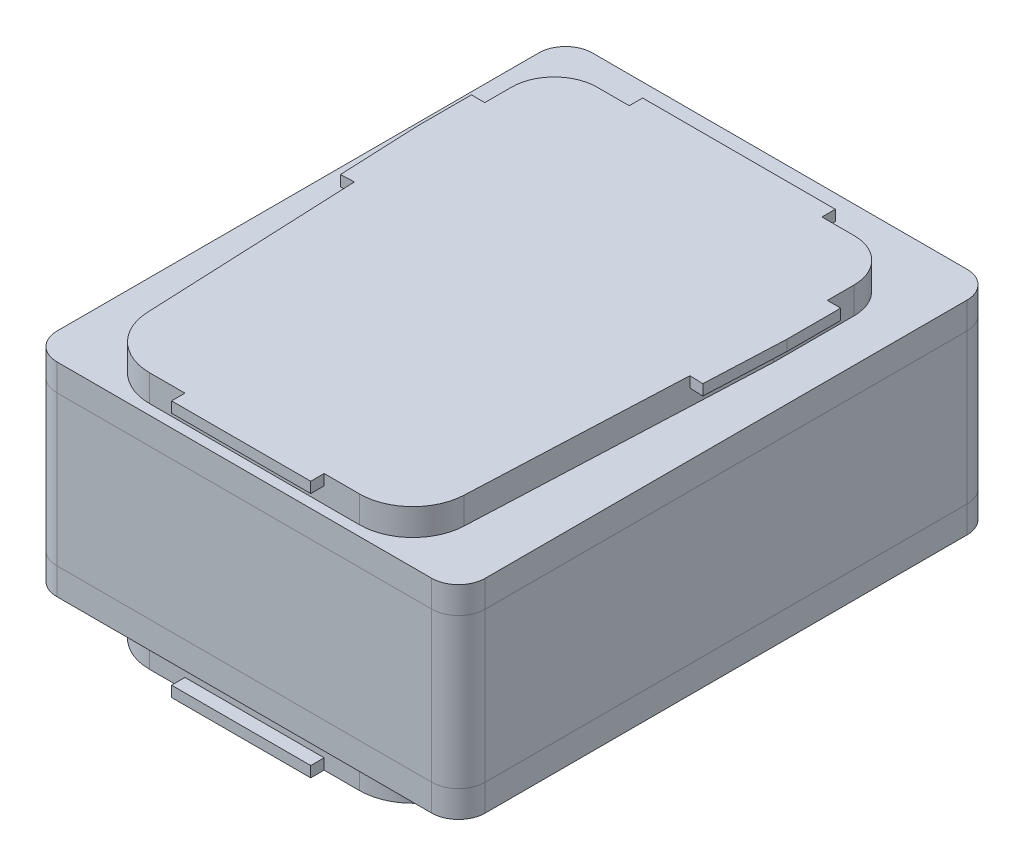
SolidWorks part; units mm, degrees
ref_plane "Front Plane" through (0, 0, 0) normal (0, 0, 1) x (1, 0, 0)
ref_plane "Top Plane" through (0, 0, 0) normal (0, 1, 0) x (1, 0, 0)
ref_plane "Right Plane" through (0, 0, 0) normal (1, 0, 0) x (0, 0, -1)
sketch "Sketch1" plane through (0, 0, 0) normal (0, 1, 0) x (1, 0, 0)
  line L0 (-32, 36) -> (-32, 21)
  line L3 (-24, 44) -> (24, 44)
  line L7 (32, 36) -> (32, 21)
  line L8 (-32, 21) -> (-29.5796, -34.4362)
  line L9 (-19.5891, -44) -> (19.5891, -44)
  line L10 (29.5796, -34.4362) -> (32, 21)
  line L11 (-24, 41) -> (24, 41)
  line L12 (29, 36) -> (29, 21.0655)
  line L13 (26.5825, -34.3053) -> (29, 21.0655)
  line L14 (-19.5891, -41) -> (19.5891, -41)
  line L15 (-29, 21.0655) -> (-26.5825, -34.3053)
  line L16 (-29, 36) -> (-29, 21.0655)
  line L17 (-35, -45.9) -> (35, -45.9)
  line L18 (-40, -40.9) -> (-40, 49.1)
  line L19 (-35, 54.1) -> (35, 54.1)
  line L20 (40, -40.9) -> (40, 49.1)
  arc A2 (-19.5891, -44) -> (-29.5796, -34.4362) centre (-19.5891, -34) cw
  arc A3 (29.5796, -34.4362) -> (19.5891, -44) centre (19.5891, -34) cw
  arc A4 (-24, 44) -> (-32, 36) centre (-24, 36) ccw
  arc A5 (32, 36) -> (24, 44) centre (24, 36) ccw
  arc A6 (29, 36) -> (24, 41) centre (24, 36) ccw
  arc A7 (26.5825, -34.3053) -> (19.5891, -41) centre (19.5891, -34) cw
  arc A8 (-19.5891, -41) -> (-26.5825, -34.3053) centre (-19.5891, -34) cw
  arc A9 (-24, 41) -> (-29, 36) centre (-24, 36) ccw
  arc A10 (-40, -40.9) -> (-35, -45.9) centre (-35, -40.9) ccw
  arc A11 (35, -45.9) -> (40, -40.9) centre (35, -40.9) ccw
  arc A12 (40, 49.1) -> (35, 54.1) centre (35, 49.1) ccw
  arc A13 (-35, 54.1) -> (-40, 49.1) centre (-35, 49.1) ccw
  point P0 (0, 0)
  point P32 (0, 4.1)
  dimension "D1" = 177.5
  dimension "D4" = 8
  dimension "D5" = 8
  dimension "D8" = 15
  dimension "D13" = 10
  dimension "D14" = 10
  dimension "D12" = 5
  dimension "D2" = 44
  dimension "D3" = 177.5
  dimension "D6" = 32
  dimension "D7" = 32
  dimension "D9" = 15
  dimension "D10" = 44
  dimension "D11" = 3
  dimension "D15" = 100
  dimension "D16" = 80
  dimension "D17" = 50
  dimension "D18" = 40
  dimension "D19" = 4.1
ref_plane "Plane1" through (0, 25, 0) normal (0, 1, 0) x (1, 0, 0)
sketch "Sketch8" plane through (0, 0, 0) normal (0, 1, 0) x (-1, 0, 0)
  line L0 (32, -36) -> (32, -21)
  line L1 (24, -44) -> (-24, -44)
  line L2 (-32, -36) -> (-32, -21)
  line L3 (32, -21) -> (29.5796, 34.4362)
  line L4 (19.5891, 44) -> (-19.5891, 44)
  line L5 (-29.5796, 34.4362) -> (-32, -21)
  line L7 (15.9, 11.8) -> (-15.9, -20) construction
  line L9 (-15.9, 11.8) -> (15.9, -20) construction
  arc A0 (19.5891, 44) -> (29.5796, 34.4362) centre (19.5891, 34) cw
  arc A1 (-29.5796, 34.4362) -> (-19.5891, 44) centre (-19.5891, 34) cw
  arc A2 (24, -44) -> (32, -36) centre (24, -36) ccw
  arc A3 (-32, -36) -> (-24, -44) centre (-24, -36) ccw
  circle A4 centre (15.9, 11.8) radius 10
  circle A8 centre (-15.9, 11.8) radius 10
  circle A9 centre (15.9, -20) radius 10
  circle A10 centre (-15.9, -20) radius 10
  point P0 (0, 0)
  point P28 (0, -4.1)
  dimension "D7" = 10
  dimension "D8" = 10
  dimension "D9" = 8
  dimension "D10" = 8
  dimension "D13" = 20
  dimension "D14" = 24
  dimension "D20" = 20
  dimension "D21" = 20
  dimension "D22" = 20
  dimension "D1" = 44
  dimension "D2" = 177.5
  dimension "D3" = 177.5
  dimension "D4" = 32
  dimension "D5" = 32
  dimension "D6" = 44
  dimension "D11" = 15
  dimension "D12" = 15
  dimension "D15" = 31.8
  dimension "D16" = 31.8
  dimension "D17" = 31.8
  dimension "D18" = 31.8
  dimension "D19" = 15.9
  dimension "D23" = 4.1
extrude "Boss-Extrude6" add sketch "Sketch8" against normal blind 5 separate body
extrude "Boss-Extrude7" add sketch "Sketch1" along normal blind 5 contours L19 A13 L18 A10 L17 A11 L20 A12 A5 L7 L10 A3 L9 A2 L8 L0 A4 L3 | L7 A5 L3 A4 L0 L8 A2 L9 A3 L10 A9 L11 A6 L12 L13 A7 L14 A8 L15 L16
ref_plane "Plane2" through (0, 38, 0) normal (0, 1, 0) x (1, 0, 0)
sketch "Sketch2" plane through (0, 25, 0) normal (0, 1, 0) x (1, 0, 0)
  line L1 (-35, -45.9) -> (35, -45.9)
  line L2 (-40, -40.9) -> (-40, 49.1)
  line L3 (-35, 54.1) -> (35, 54.1)
  line L4 (40, -40.9) -> (40, 49.1)
  arc A0 (-40, -40.9) -> (-35, -45.9) centre (-35, -40.9) ccw
  arc A1 (35, -45.9) -> (40, -40.9) centre (35, -40.9) ccw
  arc A2 (40, 49.1) -> (35, 54.1) centre (35, 49.1) ccw
  arc A3 (-35, 54.1) -> (-40, 49.1) centre (-35, 49.1) ccw
  point P0 (0, 4.1)
  dimension "D3" = 5
  dimension "D1" = 100
  dimension "D2" = 80
  dimension "D4" = 50
  dimension "D5" = 40
  dimension "D6" = 4.1
extrude "Extrude-Thin4" add sketch "Sketch2" against normal up to surface (20 mm away) and the other way blind 8 separate body thin contours L3 A2 L4 A1 L1 A0 L2 A3
sketch "Sketch10" plane through (0, 38, 0) normal (0, 1, 0) x (1, 0, 0)
  line L0 (-32, 36) -> (-32, 21)
  line L1 (-24, 44) -> (24, 44)
  line L2 (32, 36) -> (32, 21)
  line L3 (-32, 21) -> (-29.5796, -34.4362)
  line L4 (-19.5891, -44) -> (19.5891, -44)
  line L5 (29.5796, -34.4362) -> (32, 21)
  arc A0 (-19.5891, -44) -> (-29.5796, -34.4362) centre (-19.5891, -34) cw
  arc A1 (29.5796, -34.4362) -> (19.5891, -44) centre (19.5891, -34) cw
  arc A2 (-24, 44) -> (-32, 36) centre (-24, 36) ccw
  arc A3 (32, 36) -> (24, 44) centre (24, 36) ccw
  point P0 (0, 0)
  dimension "D7" = 10
  dimension "D8" = 10
  dimension "D9" = 8
  dimension "D10" = 8
  dimension "D1" = 44
  dimension "D2" = 177.5
  dimension "D3" = 177.5
  dimension "D4" = 32
  dimension "D5" = 32
  dimension "D6" = 44
  dimension "D11" = 15
  dimension "D12" = 15
extrude "Boss-Extrude8" add sketch "Sketch10" along normal blind 5 separate body
sketch "Sketch11" plane through (0, 38, 0) normal (0, 1, 0) x (1, 0, 0)
  line L0 (-35, -45.9) -> (35, -45.9)
  line L1 (-40, -40.9) -> (-40, 49.1)
  line L2 (-35, 54.1) -> (35, 54.1)
  line L3 (40, -40.9) -> (40, 49.1)
  line L4 (-35, 54.1) -> (35, 54.1) construction
  line L5 (40, -40.9) -> (40, 49.1) construction
  line L6 (-35, -45.9) -> (35, -45.9) construction
  arc A0 (-40, -40.9) -> (-35, -45.9) centre (-35, -40.9) ccw
  arc A1 (35, -45.9) -> (40, -40.9) centre (35, -40.9) ccw
  arc A2 (40, 49.1) -> (35, 54.1) centre (35, 49.1) ccw
  arc A3 (-35, 54.1) -> (-40, 49.1) centre (-35, 49.1) ccw
  dimension "D1" = 5
extrude "Boss-Extrude9" add sketch "Sketch11" against normal blind 5
sketch "Sketch13" plane through (0, 0, 0) normal (1, 0, 0) x (0, 0, -1)
  line L1 (49.1, 11.1) -> (42.6, 11.1)
  line L2 (49.1, 11.1) -> (49.1, 28.9)
  line L3 (49.1, 28.9) -> (42.6, 28.9)
  line L4 (42.6, 11.1) -> (42.6, 28.9)
  line L5 (-34.4, 11.1) -> (-40.9, 11.1)
  line L6 (-34.4, 11.1) -> (-34.4, 28.9)
  line L7 (-34.4, 28.9) -> (-40.9, 28.9)
  line L8 (-40.9, 11.1) -> (-40.9, 28.9)
  line L9 (-40.9, 33) -> (-40.9, 5) construction
  line L10 (49.1, 33) -> (49.1, 5) construction
  dimension "D1" = 17.8
  dimension "D2" = 6.5
  dimension "D3" = 11.1
  dimension "D4" = 17.8
  dimension "D5" = 6.5
  dimension "D6" = 11.1
extrude "Boss-Extrude10" add sketch "Sketch13" along normal through all and the other way through all
sketch "Sketch15" plane through (0, 11.1, 0) normal (0, -1, 0) x (1, 0, 0)
  line L0 (35, -49.1) -> (-35, -49.1) construction
  line L1 (-35, -42.6) -> (-35, -49.1) construction
  line L3 (-35, 40.9) -> (-35, 34.4) construction
  line L4 (-35, 40.9) -> (35, 40.9) construction
  line L6 (0, -26.4) -> (0, 26.4) construction
  circle A0 centre (-21.9, -44) radius 2.25
  circle A1 centre (-9.9, -44) radius 2.25
  circle A2 centre (-21.9, 35.8) radius 2.25
  circle A3 centre (-9.9, 35.8) radius 2.25
  circle A4 centre (9.9, 35.8) radius 2.25
  circle A5 centre (21.9, 35.8) radius 2.25
  circle A6 centre (9.9, -44) radius 2.25
  circle A7 centre (21.9, -44) radius 2.25
  dimension "D1" = 5.1
  dimension "D2" = 4.5
  dimension "D5" = 4.5
  dimension "D6" = 4.5
  dimension "D8" = 4.5
  dimension "D3" = 13.1
  dimension "D4" = 12
  dimension "D7" = 12
  dimension "D9" = 5.1
  dimension "D10" = 13.1
extrude "Cut-Extrude1" cut sketch "Sketch15" against normal up to surface (17.8 mm away) contours A5
sketch "Sketch17" plane through (0, -5, 0) normal (0, 1, 0) x (1, 0, 0)
  line L0 (0, 0) -> (0, 54.1) construction
  line L5 (18, 46.5) -> (18, 43.5)
  line L6 (18, 46.5) -> (-18, 46.5)
  line L7 (18, 43.5) -> (-18, 43.5)
  line L8 (-18, 46.5) -> (-18, 43.5)
  line L9 (18, 46.5) -> (-18, 43.5) construction
  line L10 (18, 43.5) -> (-18, 46.5) construction
  line L11 (-35, 54.1) -> (35, 54.1) construction
  line L12 (-13, -46.5) -> (13, -46.5)
  line L13 (-13, -46.5) -> (-13, -43.5)
  line L14 (-13, -43.5) -> (13, -43.5)
  line L15 (13, -46.5) -> (13, -43.5)
  line L16 (-13, -46.5) -> (13, -43.5) construction
  line L17 (-13, -43.5) -> (13, -46.5) construction
  line L19 (-31.5, 21.0109) -> (-30.8457, 6.0252)
  line L21 (-30.8457, 6.0252) -> (-33.8429, 5.8943)
  line L22 (-33.8429, 5.8943) -> (-34.5, 20.9454)
  line L24 (-34.5, 31.0109) -> (-34.5, 20.9454)
  line L25 (-31.5, 31.0109) -> (-34.5, 31.0109)
  line L27 (24, 44) -> (-24, 44) construction
  line L31 (29.0801, -34.4144) -> (31.5, 21.0109) construction
  line L32 (31.5, 21.0109) -> (31.5, 31.0109) construction
  line L33 (-31.5, 21.0109) -> (-31.5, 31.0109)
  line L40 (31.5, 21.0109) -> (31.5, 31.0109)
  line L41 (31.5, 31.0109) -> (34.5, 31.0109)
  line L46 (34.5, 31.0109) -> (34.5, 20.9454)
  line L47 (31.5, 21.0109) -> (30.8457, 6.0252)
  line L48 (30.8457, 6.0252) -> (33.8429, 5.8943)
  line L49 (33.8429, 5.8943) -> (34.5, 20.9454)
  point P1 (0, 45)
  point P3 (0, -45)
  dimension "D1" = 36
  dimension "D2" = 3
  dimension "D3" = 3
  dimension "D4" = 26
  dimension "D5" = 0.5
  dimension "D7" = 3
  dimension "D8" = 3
  dimension "D12" = 10
  dimension "D13" = 15
sketch "Sketch18" plane through (0, 43, 0) normal (0, 1, 0) x (1, 0, 0)
  line L5 (18, 46.5) -> (18, 43.5)
  line L6 (18, 46.5) -> (-18, 46.5)
  line L7 (18, 43.5) -> (-18, 43.5)
  line L8 (-18, 46.5) -> (-18, 43.5)
  line L9 (18, 46.5) -> (-18, 43.5) construction
  line L10 (18, 43.5) -> (-18, 46.5) construction
  line L12 (-13, -46.5) -> (13, -46.5)
  line L13 (-13, -46.5) -> (-13, -43.5)
  line L14 (-13, -43.5) -> (13, -43.5)
  line L15 (13, -46.5) -> (13, -43.5)
  line L16 (-13, -46.5) -> (13, -43.5) construction
  line L17 (-13, -43.5) -> (13, -46.5) construction
  line L19 (-31.5, 21.0109) -> (-30.8457, 6.0252)
  line L21 (-30.8457, 6.0252) -> (-33.8429, 5.8943)
  line L22 (-33.8429, 5.8943) -> (-34.5, 20.9454)
  line L24 (-34.5, 31.0109) -> (-34.5, 20.9454)
  line L25 (-31.5, 31.0109) -> (-34.5, 31.0109)
  line L31 (29.0801, -34.4144) -> (31.5, 21.0109) construction
  line L32 (31.5, 21.0109) -> (31.5, 31.0109) construction
  line L33 (-31.5, 21.0109) -> (-31.5, 31.0109)
  line L40 (31.5, 21.0109) -> (31.5, 31.0109)
  line L41 (31.5, 31.0109) -> (34.5, 31.0109)
  line L46 (34.5, 31.0109) -> (34.5, 20.9454)
  line L47 (31.5, 21.0109) -> (30.8457, 6.0252)
  line L48 (30.8457, 6.0252) -> (33.8429, 5.8943)
  line L49 (33.8429, 5.8943) -> (34.5, 20.9454)
  point P1 (0, 45)
  point P3 (0, -45)
  dimension "D1" = 36
  dimension "D2" = 3
  dimension "D3" = 3
  dimension "D4" = 26
  dimension "D7" = 3
  dimension "D8" = 3
  dimension "D12" = 10
  dimension "D13" = 15
extrude "Boss-Extrude11" add sketch "Sketch17" along normal blind 2
extrude "Boss-Extrude12" add sketch "Sketch18" against normal blind 2
ref_plane "Plane6" through (0, 5, 0) normal (0, 1, 0) x (1, 0, 0)
